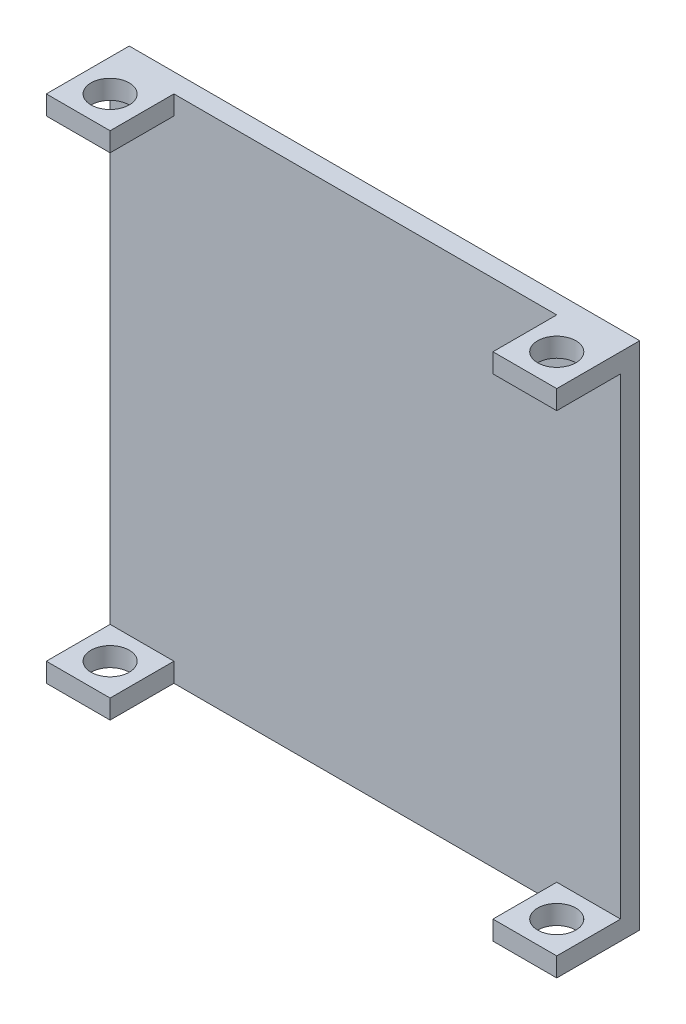
SolidWorks part; units mm, degrees
ref_plane "Front Plane" through (0, 0, 0) normal (0, 0, 1) x (1, 0, 0)
ref_plane "Top Plane" through (0, 0, 0) normal (0, 1, 0) x (1, 0, 0)
ref_plane "Right Plane" through (0, 0, 0) normal (1, 0, 0) x (0, 0, -1)
sketch "Sketch1" plane through (0, 0, 0) normal (0, 0, 1) x (1, 0, 0)
  line L1 (40, 40) -> (-40, 40)
  line L2 (40, 40) -> (40, -40)
  line L3 (40, -40) -> (-40, -40)
  line L4 (-40, 40) -> (-40, -40)
  dimension "D1" = 80
  dimension "D2" = 80
  dimension "D3" = 40
  dimension "D4" = 40
extrude "Boss-Extrude1" add sketch "Sketch1" along normal blind 3
sketch "Sketch9" plane through (0, 40, 0) normal (0, 1, 0) x (1, 0, 0)
  line L1 (-40, -3) -> (-30, -3)
  line L2 (-40, -3) -> (-40, -13)
  line L3 (-40, -13) -> (-30, -13)
  line L4 (-30, -3) -> (-30, -13)
  line L5 (40, -3) -> (30, -3)
  line L6 (40, -3) -> (40, -13)
  line L7 (40, -13) -> (30, -13)
  line L8 (30, -3) -> (30, -13)
  circle A0 centre (35, -8) radius 3
  circle A1 centre (-35, -8) radius 3
  dimension "D5" = 6
  dimension "D8" = 6
  dimension "D1" = 10
  dimension "D2" = 10
  dimension "D3" = 10
  dimension "D4" = 10
  dimension "D6" = 5
  dimension "D7" = 5
  dimension "D9" = 5
  dimension "D10" = 5
extrude "Boss-Extrude8" add sketch "Sketch9" against normal blind 3
sketch "Sketch10" plane through (0, -40, 0) normal (0, -1, 0) x (1, 0, 0)
  line L0 (-30, 3) -> (-30, 13)
  line L1 (-30, 13) -> (-40, 13)
  line L2 (-40, 13) -> (-40, 3)
  line L3 (-40, 3) -> (-30, 3)
  line L4 (30, 3) -> (30, 13)
  line L5 (30, 13) -> (40, 13)
  line L6 (40, 13) -> (40, 3)
  line L7 (40, 3) -> (30, 3)
  circle A0 centre (-35, 8) radius 3
  circle A1 centre (35, 8) radius 3
extrude "Boss-Extrude9" add sketch "Sketch10" against normal blind 3
